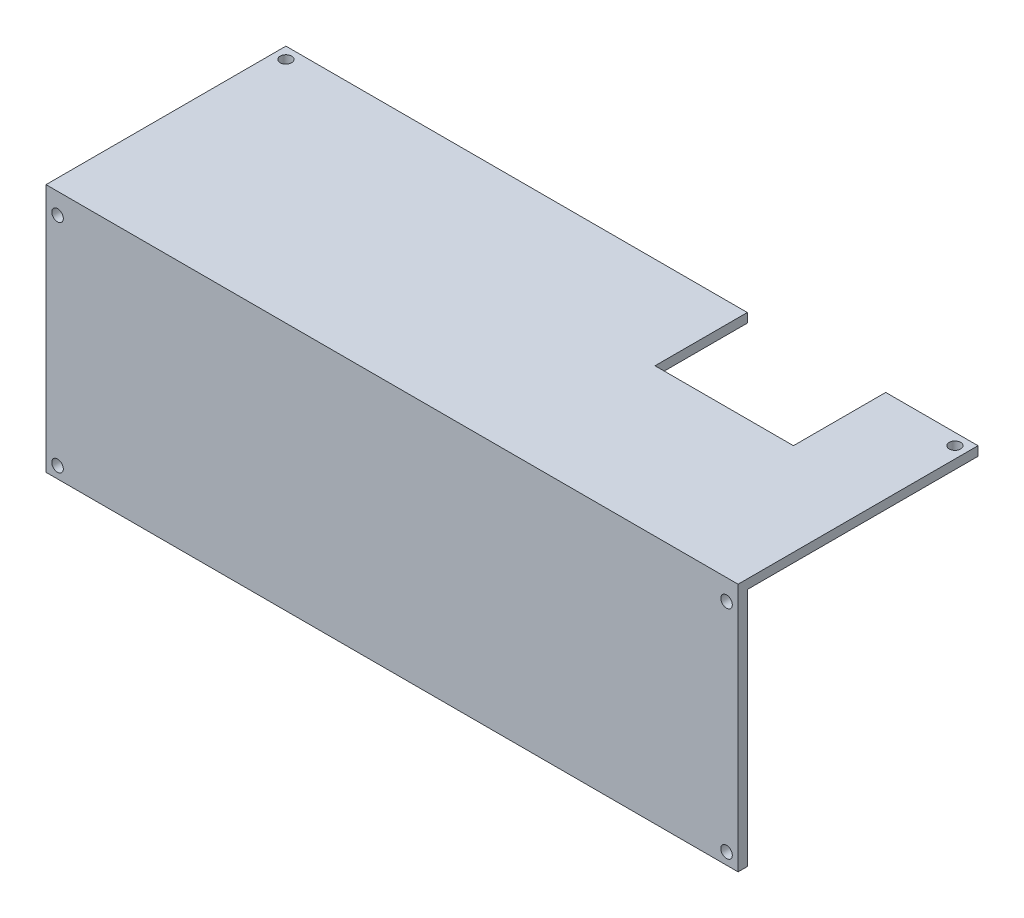
SolidWorks part; units mm, degrees
ref_plane "Ebene vorne" through (0, 0, 0) normal (0, 0, 1) x (1, 0, 0)
ref_plane "Ebene oben" through (0, 0, 0) normal (0, 1, 0) x (1, 0, 0)
ref_plane "Ebene rechts" through (0, 0, 0) normal (1, 0, 0) x (0, 0, -1)
sketch "Skizze1" plane through (0, 0, 0) normal (0, 0, 1) x (1, 0, 0)
  line L0 (145, 52) -> (5, 52)
  line L10 (148, 39.8586) -> (148, 12.1414)
  line L11 (137.8586, 2) -> (12.1414, 2)
  line L12 (2, 12.1414) -> (2, 39.8586)
  line L13 (5, 47) -> (5, 52)
  line L14 (5, 52) -> (0, 52)
  line L15 (0, 52) -> (0, 0)
  line L16 (0, 0) -> (150, 0)
  line L17 (150, 0) -> (150, 52)
  line L18 (150, 52) -> (145, 52)
  line L19 (145, 52) -> (145, 47)
  line L20 (148, 39.8586) -> (148, 12.1414)
  line L21 (137.8586, 2) -> (12.1414, 2)
  line L22 (2, 12.1414) -> (2, 39.8586)
  line L23 (5, 47) -> (5, 52)
  line L24 (5, 52) -> (0, 52)
  line L25 (0, 52) -> (0, 0)
  line L26 (0, 0) -> (150, 0)
  line L27 (150, 0) -> (150, 52)
  line L28 (150, 52) -> (145, 52)
  line L29 (145, 52) -> (145, 47)
  circle A0 centre (147.5, 2.5) radius 1.25 construction
  circle A1 centre (147.5, 2.5) radius 1.25
  circle A2 centre (147.5, 49.5) radius 1.25 construction
  circle A3 centre (147.5, 49.5) radius 1.25
  circle A4 centre (2.5, 2.5) radius 1.25 construction
  circle A5 centre (2.5, 2.5) radius 1.25
  arc A6 (145, 5) -> (148, 12.1414) centre (138, 12.1414) ccw
  arc A7 (137.8586, 2) -> (145, 5) centre (137.8586, 12) ccw
  arc A8 (5, 5) -> (12.1414, 2) centre (12.1414, 12) ccw
  arc A9 (2, 12.1414) -> (5, 5) centre (12, 12.1414) ccw
  arc A10 (5, 47) -> (2, 39.8586) centre (12, 39.8586) ccw
  arc A11 (148, 39.8586) -> (145, 47) centre (138, 39.8586) ccw
  arc A12 (145, 5) -> (148, 12.1414) centre (138, 12.1414) ccw
  arc A13 (137.8586, 2) -> (145, 5) centre (137.8586, 12) ccw
  arc A14 (5, 5) -> (12.1414, 2) centre (12.1414, 12) ccw
  arc A15 (2, 12.1414) -> (5, 5) centre (12, 12.1414) ccw
  arc A16 (5, 47) -> (2, 39.8586) centre (12, 39.8586) ccw
  arc A17 (148, 39.8586) -> (145, 47) centre (138, 39.8586) ccw
  circle A18 centre (2.5, 49.5) radius 1.25 construction
  circle A19 centre (2.5, 49.5) radius 1.25
  dimension "D1" = 0
extrude "Aufsatz-Linear austragen1" add sketch "Skizze1" along normal blind 2 contours L20 A17 L29 L0 L23 A16 L22 A15 A14 L21 A13 A12 | A17 L20 A12 A13 L21 A14 A15 L22 A16 L23 L24 L25 L26 L27 L28 L29 A19 A5 A3 A1
sketch "Skizze2" plane through (0, 52, 0) normal (0, 1, 0) x (1, 0, 0)
  line L1 (150, -2) -> (0, -2)
  line L2 (150, -2) -> (150, 50)
  line L3 (150, 50) -> (0, 50)
  line L4 (0, -2) -> (0, 50)
  line L5 (150, -2) -> (0, 50) construction
  line L6 (150, 50) -> (0, -2) construction
  point P4 (75, 24)
extrude "Aufsatz-Linear austragen2" add sketch "Skizze2" along normal blind 2
sketch "Skizze3" plane through (0, 52, 0) normal (0, -1, 0) x (1, 0, 0)
  line L1 (130, -50) -> (100, -50)
  line L2 (130, -50) -> (130, -30)
  line L3 (130, -30) -> (100, -30)
  line L4 (150, -50) -> (150, 0)
  line L5 (150, 0) -> (0, 0)
  line L6 (0, 0) -> (0, -50)
  line L7 (0, -50) -> (150, -50)
  line L8 (150, -50) -> (150, 0)
  line L9 (150, 0) -> (0, 0)
  line L10 (0, 0) -> (0, -50)
  line L11 (0, -50) -> (150, -50)
  line L12 (100, -50) -> (100, -30)
  line L13 (130, -50) -> (100, -30) construction
  line L14 (130, -30) -> (100, -50) construction
  point P8 (115, -40)
  line M10 (0, -50) -> (150, -50)
  dimension "D2" = 20
  dimension "D3" = 20
  dimension "D4" = 30
  dimension "D1" = 0
extrude "Schnitt-Linear austragen1" cut sketch "Skizze3" against normal blind 2 contours L12 L2 L3 M10
sketch "Skizze4" plane through (0, 52, 0) normal (0, -1, 0) x (1, 0, 0)
  line L8 (100, -50) -> (100, -30)
  line L9 (100, -30) -> (130, -30)
  line L10 (130, -30) -> (130, -50)
  line L11 (130, -50) -> (150, -50)
  line L12 (150, -50) -> (150, 0)
  line L13 (150, 0) -> (0, 0)
  line L14 (0, 0) -> (0, -50)
  line L15 (0, -50) -> (100, -50)
  line L16 (100, -50) -> (100, -30)
  line L17 (100, -30) -> (130, -30)
  line L18 (130, -30) -> (130, -50)
  line L19 (130, -50) -> (150, -50)
  line L20 (150, -50) -> (150, 0)
  line L21 (150, 0) -> (0, 0)
  line L22 (0, 0) -> (0, -50)
  line L23 (0, -50) -> (100, -50)
  dimension "D1" = 0
sketch "Skizze5" plane through (0, 54, 0) normal (0, 1, 0) x (1, 0, 0)
  line L0 (130, 50) -> (150, 50) construction
  line L2 (150, -2) -> (150, 50) construction
  circle A0 centre (147.5, 47.5) radius 1.25
  circle A1 centre (2.5, 47.5) radius 1.25
  dimension "D1" = 2.5
  dimension "D4" = 2.5
  dimension "D2" = 2.5
  dimension "D3" = 2.5
extrude "Schnitt-Linear austragen2" cut sketch "Skizze5" against normal blind 2
